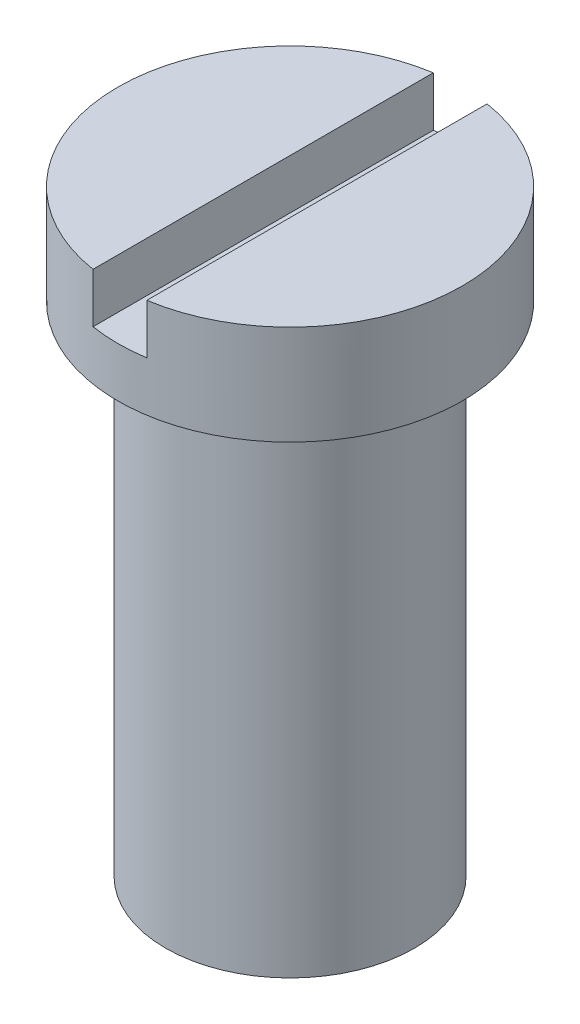
SolidWorks part; units mm, degrees
ref_plane "Front Plane" through (0, 0, 0) normal (0, 0, 1) x (1, 0, 0)
ref_plane "Top Plane" through (0, 0, 0) normal (0, 1, 0) x (1, 0, 0)
ref_plane "Right Plane" through (0, 0, 0) normal (1, 0, 0) x (0, 0, -1)
sketch "Sketch1" plane through (0, 0, 0) normal (0, 0, 1) x (1, 0, 0)
  line L0 (0, 0) -> (0, 12) construction
  line L1 (0, 12) -> (3.46, 12)
  line L2 (3.46, 12) -> (3.46, 10)
  line L3 (3.46, 10) -> (2.5, 10)
  line L4 (2.5, 10) -> (2.5, 0)
  line L5 (2.5, 0) -> (0, 0)
  line L6 (0, 0) -> (0, 12)
  dimension "D1" = 12
  dimension "D2" = 5
  dimension "D3" = 3.46
  dimension "D4" = 2
revolve "Revolve1" add sketch "Sketch1" angle 360 about L0
sketch "Sketch2" plane through (0, 0, 0) normal (0, 0, 1) x (1, 0, 0)
  line L0 (3.46, 12) -> (-3.46, 12) construction
  line L1 (-0.54, 12) -> (0.54, 12)
  line L2 (-0.54, 12) -> (-0.54, 11)
  line L3 (-0.54, 11) -> (0.54, 11)
  line L4 (0.54, 12) -> (0.54, 11)
  point P6 (0, 11)
  dimension "D1" = 1.08
  dimension "D2" = 1
extrude "Cut-Extrude1" cut sketch "Sketch2" against normal up to next and the other way up to next
